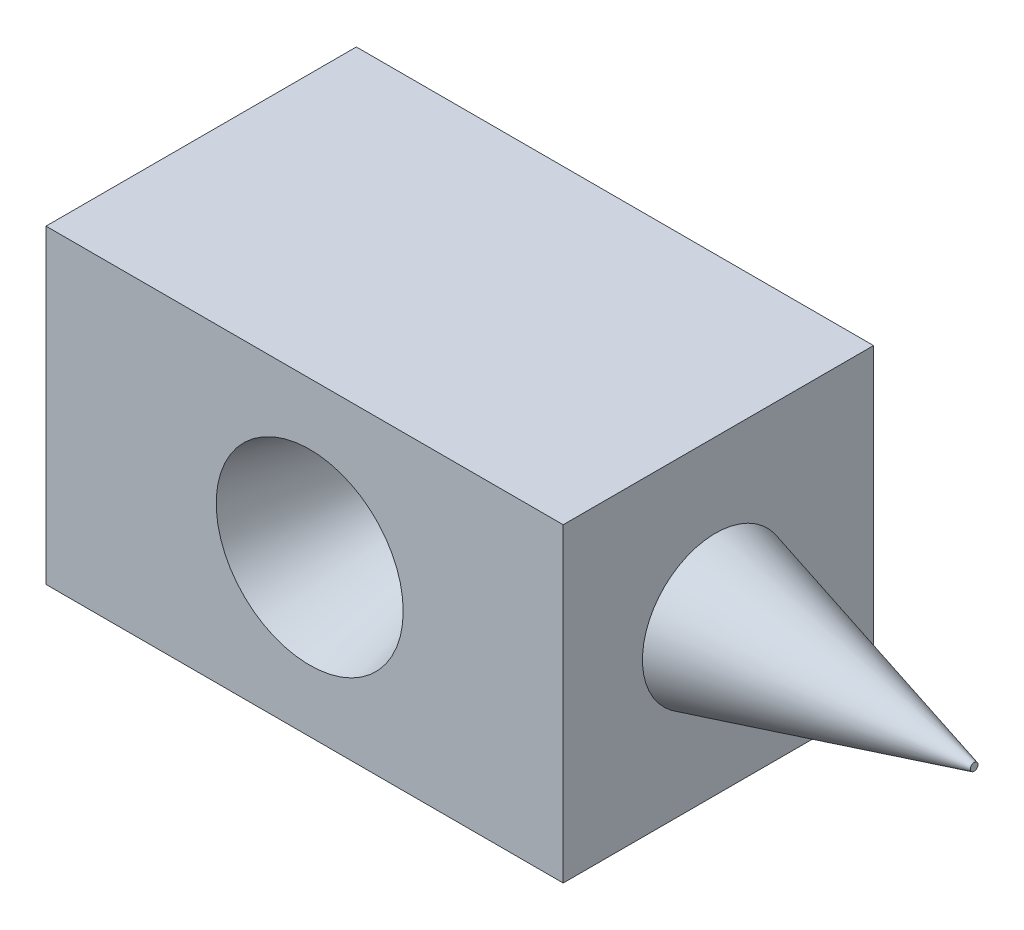
SolidWorks part; units mm, degrees
ref_plane "Front Plane" through (0, 0, 0) normal (0, 0, 1) x (1, 0, 0)
ref_plane "Top Plane" through (0, 0, 0) normal (0, 1, 0) x (1, 0, 0)
ref_plane "Right Plane" through (0, 0, 0) normal (1, 0, 0) x (0, 0, -1)
sketch "Sketch1" plane through (0, 0, 0) normal (0, 0, 1) x (1, 0, 0)
  line L0 (0, 0) -> (0, 76.2)
  line L1 (0, 76.2) -> (127, 76.2)
  line L2 (127, 76.2) -> (127, 0)
  line L3 (127, 0) -> (0, 0)
  dimension "D1" = 76.2
  dimension "D2" = 127
extrude "Boss-Extrude1" add sketch "Sketch1" along normal blind 76.2
sketch "Sketch2" plane through (0, 0, 76.2) normal (0, 0, 1) x (1, 0, 0)
  circle A0 centre (64.7532, 38.1556) radius 22.958
sketch "Sketch3" plane through (127, 0, 0) normal (1, 0, 0) x (0, 0, -1)
  circle A0 centre (-38.7913, 37.7544) radius 17.9551
extrude "Cut-Extrude1" cut sketch "Sketch2" against normal blind 50.8 draft 15
extrude "Boss-Extrude2" add sketch "Sketch3" along normal blind 63.5 draft 15
